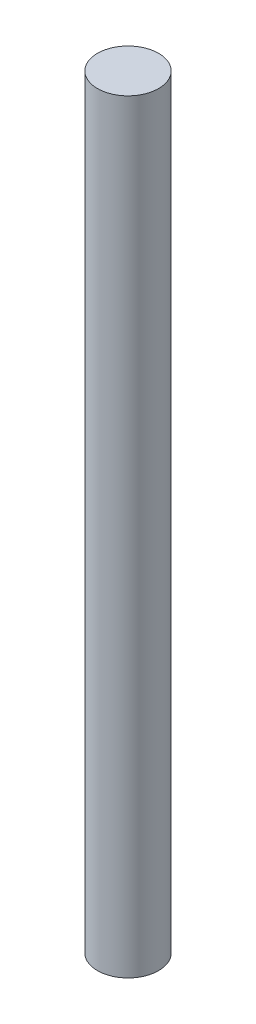
SolidWorks part; units mm, degrees
ref_plane "Front Plane" through (0, 0, 0) normal (0, 0, 1) x (1, 0, 0)
ref_plane "Top Plane" through (0, 0, 0) normal (0, 1, 0) x (1, 0, 0)
ref_plane "Right Plane" through (0, 0, 0) normal (1, 0, 0) x (0, 0, -1)
sketch "Sketch1" plane through (0, 0, 0) normal (0, 1, 0) x (1, 0, 0)
  circle A0 centre (0, 0) radius 6.35
  dimension "D1" = 12.7
extrude "Boss-Extrude1" add sketch "Sketch1" along normal blind 158.75
cosmetic thread "Cosmetic Thread1" parameters "D1"=19.05, "D2"=10.3734
cosmetic thread "Cosmetic Thread2" parameters "D1"=19.05, "D2"=10.3734
